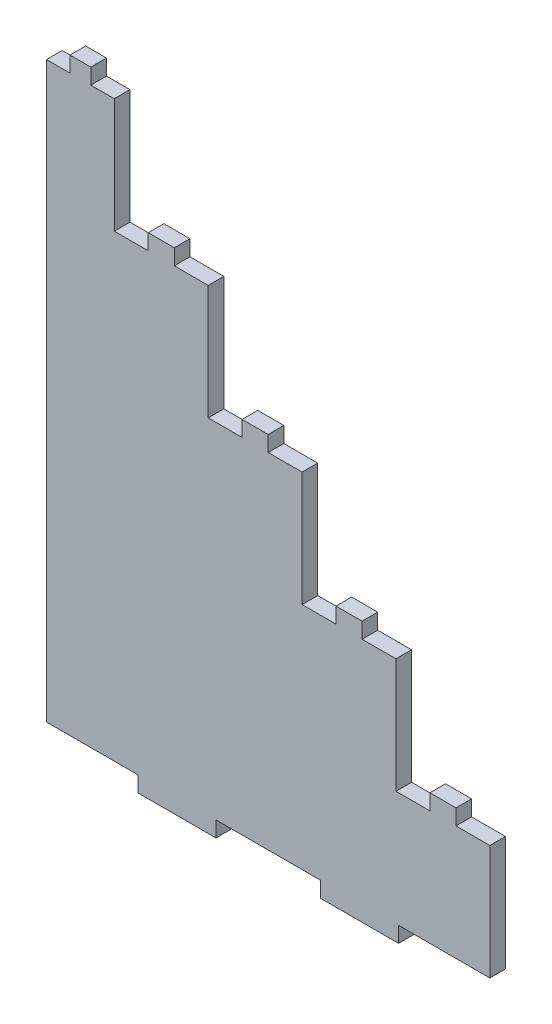
SolidWorks part; units mm, degrees
ref_plane "Plan de face" through (0, 0, 0) normal (0, 0, 1) x (1, 0, 0)
ref_plane "Plan de dessus" through (0, 0, 0) normal (0, 1, 0) x (1, 0, 0)
ref_plane "Plan de droite" through (0, 0, 0) normal (1, 0, 0) x (0, 0, -1)
sketch "Esquisse1" plane through (0, 0, 0) normal (0, 0, 1) x (1, 0, 0)
  line L0 (0, 220) -> (26, 220)
  line L1 (0, 0) -> (170, 0)
  line L2 (0, 0) -> (0, 220)
  line L3 (26, 220) -> (26, 176)
  line L4 (26, 176) -> (62, 176)
  line L5 (62, 176) -> (62, 132)
  line L6 (62, 132) -> (98, 132)
  line L7 (98, 132) -> (98, 88)
  line L8 (98, 88) -> (134, 88)
  line L9 (134, 88) -> (134, 44)
  line L10 (134, 44) -> (170, 44)
  line L11 (170, 44) -> (170, 0)
  dimension "D1" = 220
  dimension "D2" = 170
  dimension "D3" = 36
  dimension "D4" = 36
  dimension "D5" = 36
  dimension "D6" = 36
  dimension "D7" = 44
  dimension "D8" = 44
  dimension "D9" = 44
  dimension "D10" = 44
  dimension "D11" = 44
  dimension "D12" = 26
extrude "Boss.-Extru.1" add sketch "Esquisse1" along normal blind 6
sketch "Esquisse2" plane through (0, 0, 0) normal (0, -1, 0) x (1, 0, 0)
  line L1 (35, 6) -> (65, 6)
  line L2 (35, 6) -> (35, 0)
  line L3 (35, 0) -> (65, 0)
  line L4 (65, 6) -> (65, 0)
  line L6 (0, 6) -> (170, 6) construction
  line L7 (0, 0) -> (170, 0) construction
  line L8 (0, 6) -> (0, 0) construction
  line L9 (105, 0) -> (135, 0)
  line L10 (105, 0) -> (105, 6)
  line L11 (105, 6) -> (135, 6)
  line L12 (135, 0) -> (135, 6)
  line L13 (170, 6) -> (170, 0) construction
  point P12 (0, 3)
  dimension "D1" = 6
  dimension "D2" = 30
  dimension "D3" = 6
  dimension "D4" = 30
  dimension "D5" = 35
  dimension "D6" = 35
  dimension "D7" = 40
extrude "Boss.-Extru.2" add sketch "Esquisse2" along normal blind 6
sketch "Esquisse3" plane through (0, 220, 0) normal (0, 1, 0) x (1, 0, 0)
  line L1 (26, -6) -> (0, -6) construction
  line L2 (9, -6) -> (17, -6)
  line L3 (9, -6) -> (9, 0)
  line L4 (9, 0) -> (17, 0)
  line L9 (26, -6) -> (26, 0) construction
  line L10 (17, -6) -> (17, 0)
  line L11 (26, 0) -> (0, 0) construction
  line L12 (0, -6) -> (0, 0) construction
  point P13 (26, -3)
  dimension "D1" = 9
  dimension "D2" = 9
  dimension "D3" = 8
extrude "Boss.-Extru.3" add sketch "Esquisse3" along normal blind 6
sketch "Esquisse4" plane through (0, 176, 0) normal (0, 1, 0) x (1, 0, 0)
  line L0 (62, -6) -> (26, -6) construction
  line L1 (39, -6) -> (49, -6)
  line L2 (39, -6) -> (39, 0)
  line L3 (39, 0) -> (49, 0)
  line L4 (49, -6) -> (49, 0)
  line L5 (62, 0) -> (26, 0) construction
  line L6 (26, -6) -> (26, 0) construction
  line L7 (62, -6) -> (62, 0) construction
  point P8 (26, -3)
  dimension "D1" = 10
  dimension "D2" = 13
  dimension "D3" = 13
extrude "Boss.-Extru.4" add sketch "Esquisse4" along normal blind 6
sketch "Esquisse5" plane through (0, 132, 0) normal (0, 1, 0) x (1, 0, 0)
  line L0 (98, -6) -> (62, -6) construction
  line L1 (75, -6) -> (85, -6)
  line L2 (75, -6) -> (75, 0)
  line L3 (75, 0) -> (85, 0)
  line L4 (85, -6) -> (85, 0)
  line L5 (98, 0) -> (62, 0) construction
  line L6 (62, -6) -> (62, 0) construction
  dimension "D1" = 13
  dimension "D2" = 10
extrude "Boss.-Extru.5" add sketch "Esquisse5" along normal blind 6
sketch "Esquisse6" plane through (0, 88, 0) normal (0, 1, 0) x (1, 0, 0)
  line L0 (134, -6) -> (98, -6) construction
  line L1 (111, -6) -> (121, -6)
  line L2 (111, -6) -> (111, 0)
  line L3 (111, 0) -> (121, 0)
  line L4 (121, -6) -> (121, 0)
  line L5 (134, 0) -> (98, 0) construction
  line L6 (98, -6) -> (98, 0) construction
  point P8 (98, -3)
  dimension "D1" = 13
  dimension "D2" = 10
extrude "Boss.-Extru.6" add sketch "Esquisse6" along normal blind 6
sketch "Esquisse7" plane through (0, 44, 0) normal (0, 1, 0) x (1, 0, 0)
  line L0 (170, -6) -> (134, -6) construction
  line L1 (147, -6) -> (157, -6)
  line L2 (147, -6) -> (147, 0)
  line L3 (147, 0) -> (157, 0)
  line L4 (157, -6) -> (157, 0)
  line L5 (170, 0) -> (134, 0) construction
  line L6 (134, -6) -> (134, 0) construction
  dimension "D1" = 13
  dimension "D2" = 10
extrude "Boss.-Extru.7" add sketch "Esquisse7" along normal blind 6
